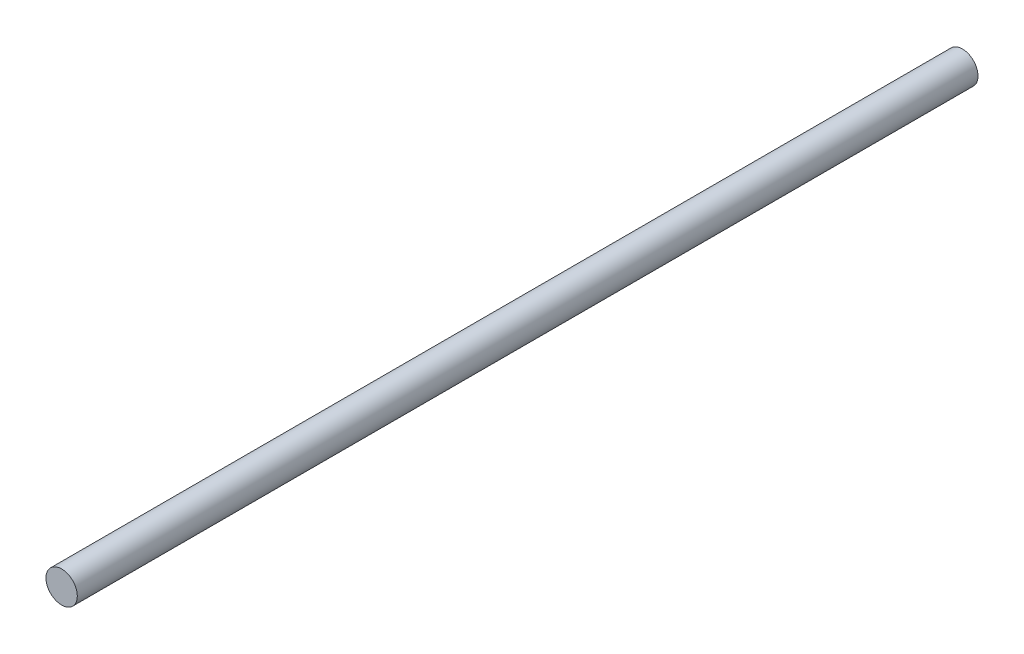
SolidWorks part; units mm, degrees
ref_plane "正面" through (0, 0, 0) normal (0, 0, 1) x (1, 0, 0)
ref_plane "平面" through (0, 0, 0) normal (0, 1, 0) x (1, 0, 0)
ref_plane "右側面" through (0, 0, 0) normal (1, 0, 0) x (0, 0, -1)
sketch "Sketch1" plane through (0, 0, 0) normal (0, 0, 1) x (1, 0, 0)
  circle A0 centre (0, 0) radius 0.4
  dimension "D1" = 0.8
extrude "Boss-Extrude1" add sketch "Sketch1" along normal blind 23
